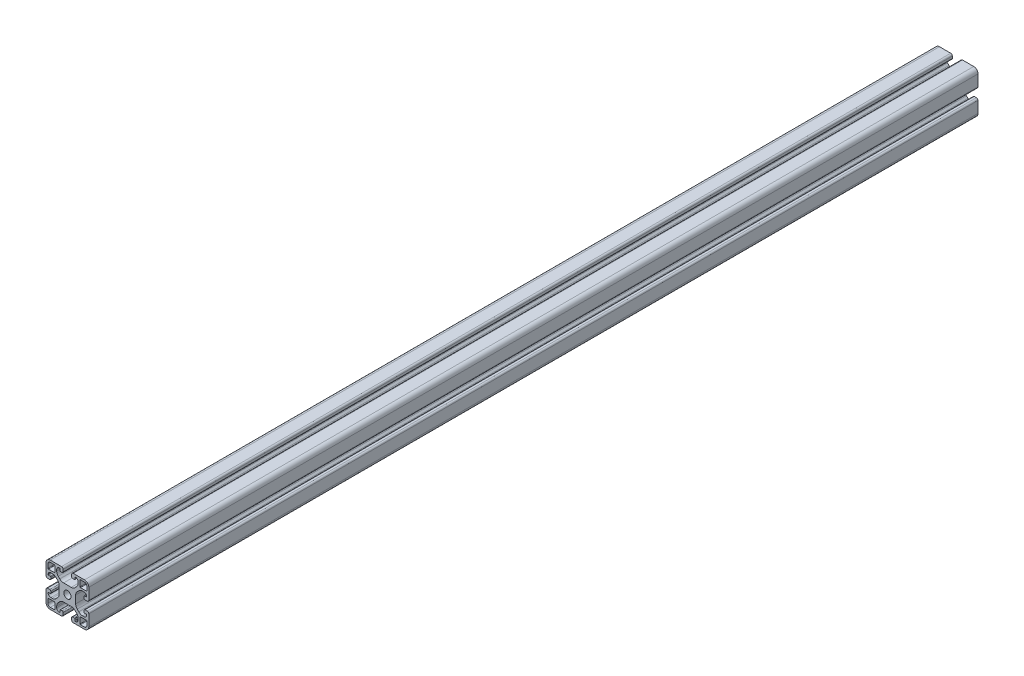
SolidWorks part; units mm, degrees
ref_plane "Plan de face" through (0, 0, 0) normal (0, 0, 1) x (1, 0, 0)
ref_plane "Plan de dessus" through (0, 0, 0) normal (0, 1, 0) x (1, 0, 0)
ref_plane "Plan de droite" through (0, 0, 0) normal (1, 0, 0) x (0, 0, -1)
ref_plane "Plan1" through (0, 0, -30) normal (0, 0, -1) x (-1, 0, 0)
sketch "Esquisse1" plane through (0, 0, -30) normal (0, 0, -1) x (-1, 0, 0)
  line L0 (-4.5, 15) -> (-4.5, 13.5)
  line L1 (-4, 13) -> (-2.5, 13)
  line L2 (-4.5, 10) -> (-5.8076, 10)
  line L3 (-9.3431, 11.4645) -> (-10.7855, 12.9069)
  line L4 (-12.25, 16.4424) -> (-12.25, 23.5576)
  line L5 (-10.7855, 27.0931) -> (-9.3431, 28.5355)
  line L6 (-5.8076, 30) -> (-4.5, 30)
  line L7 (-2.5, 27) -> (-4, 27)
  line L8 (-4.5, 26.5) -> (-4.5, 25)
  line L9 (-3.5, 24) -> (-1.5, 24)
  line L10 (0, 25.5) -> (0, 36)
  line L11 (-4, 40) -> (-14.5, 40)
  line L12 (-16, 38.5) -> (-16, 36.5)
  line L13 (-15, 35.5) -> (-13.5, 35.5)
  line L14 (-13, 36) -> (-13, 37.5)
  line L15 (-10, 35.5) -> (-10, 34.1924)
  line L16 (-11.4645, 30.6569) -> (-12.9069, 29.2145)
  line L17 (-16.4424, 27.75) -> (-23.5576, 27.75)
  line L18 (-27.0931, 29.2145) -> (-28.5355, 30.6569)
  line L19 (-30, 34.1924) -> (-30, 35.5)
  line L20 (-27, 37.5) -> (-27, 36)
  line L21 (-26.5, 35.5) -> (-25, 35.5)
  line L22 (-24, 36.5) -> (-24, 38.5)
  line L23 (-25.5, 40) -> (-36, 40)
  line L24 (-40, 36) -> (-40, 25.5)
  line L25 (-38.5, 24) -> (-36.5, 24)
  line L26 (-35.5, 25) -> (-35.5, 26.5)
  line L27 (-36, 27) -> (-37.5, 27)
  line L28 (-35.5, 30) -> (-34.1924, 30)
  line L29 (-30.6569, 28.5355) -> (-29.2145, 27.0931)
  line L30 (-27.75, 23.5576) -> (-27.75, 16.4424)
  line L31 (-29.2145, 12.9069) -> (-30.6569, 11.4645)
  line L32 (-34.1924, 10) -> (-35.5, 10)
  line L33 (-37.5, 13) -> (-36, 13)
  line L34 (-35.5, 13.5) -> (-35.5, 15)
  line L35 (-36.5, 16) -> (-38.5, 16)
  line L36 (-40, 14.5) -> (-40, 4)
  line L37 (-36, 0) -> (-25.5, 0)
  line L38 (-24, 1.5) -> (-24, 3.5)
  line L39 (-25, 4.5) -> (-26.5, 4.5)
  line L40 (-27, 4) -> (-27, 2.5)
  line L41 (-30, 4.5) -> (-30, 5.8076)
  line L42 (-28.5355, 9.3431) -> (-27.0931, 10.7855)
  line L43 (-23.5576, 12.25) -> (-16.4424, 12.25)
  line L44 (-12.9069, 10.7855) -> (-11.4645, 9.3431)
  line L45 (-10, 5.8076) -> (-10, 4.5)
  line L46 (-13, 2.5) -> (-13, 4)
  line L47 (-13.5, 4.5) -> (-15, 4.5)
  line L48 (-16, 3.5) -> (-16, 1.5)
  line L49 (-14.5, 0) -> (-4, 0)
  line L50 (0, 4) -> (0, 14.5)
  line L51 (-1.5, 16) -> (-3.5, 16)
  line L52 (-4, 1.8) -> (-7.7, 1.8)
  line L53 (-8.2, 2.3) -> (-8.2, 7.7)
  line L54 (-7.7, 8.2) -> (-2.3, 8.2)
  line L55 (-1.8, 7.7) -> (-1.8, 4)
  line L56 (-38.2, 4) -> (-38.2, 7.7)
  line L57 (-37.7, 8.2) -> (-32.3, 8.2)
  line L58 (-31.8, 7.7) -> (-31.8, 2.3)
  line L59 (-32.3, 1.8) -> (-36, 1.8)
  line L60 (-36, 38.2) -> (-32.3, 38.2)
  line L61 (-31.8, 37.7) -> (-31.8, 32.3)
  line L62 (-32.3, 31.8) -> (-37.7, 31.8)
  line L63 (-38.2, 32.3) -> (-38.2, 36)
  line L64 (-1.8, 36) -> (-1.8, 32.3)
  line L65 (-2.3, 31.8) -> (-7.7, 31.8)
  line L66 (-8.2, 32.3) -> (-8.2, 37.7)
  line L67 (-7.7, 38.2) -> (-4, 38.2)
  arc A0 (-4.5, 13.5) -> (-4, 13) centre (-4, 13.5) ccw
  arc A1 (-2.5, 13) -> (-2, 12.5) centre (-2.5, 12.5) cw
  arc A2 (-2, 12.5) -> (-4.5, 10) centre (-4.5, 12.5) cw
  arc A3 (-5.8076, 10) -> (-9.3431, 11.4645) centre (-5.8076, 15) cw
  arc A4 (-10.7855, 12.9069) -> (-12.25, 16.4424) centre (-7.25, 16.4424) cw
  arc A5 (-12.25, 23.5576) -> (-10.7855, 27.0931) centre (-7.25, 23.5576) cw
  arc A6 (-9.3431, 28.5355) -> (-5.8076, 30) centre (-5.8076, 25) cw
  arc A7 (-4.5, 30) -> (-2, 27.5) centre (-4.5, 27.5) cw
  arc A8 (-2, 27.5) -> (-2.5, 27) centre (-2.5, 27.5) cw
  arc A9 (-4, 27) -> (-4.5, 26.5) centre (-4, 26.5) ccw
  arc A10 (-4.5, 25) -> (-3.5, 24) centre (-3.5, 25) ccw
  arc A11 (-1.5, 24) -> (0, 25.5) centre (-1.5, 25.5) ccw
  arc A12 (0, 36) -> (-4, 40) centre (-4, 36) ccw
  arc A13 (-14.5, 40) -> (-16, 38.5) centre (-14.5, 38.5) ccw
  arc A14 (-16, 36.5) -> (-15, 35.5) centre (-15, 36.5) ccw
  arc A15 (-13.5, 35.5) -> (-13, 36) centre (-13.5, 36) ccw
  arc A16 (-13, 37.5) -> (-12.5, 38) centre (-12.5, 37.5) cw
  arc A17 (-12.5, 38) -> (-10, 35.5) centre (-12.5, 35.5) cw
  arc A18 (-10, 34.1924) -> (-11.4645, 30.6569) centre (-15, 34.1924) cw
  arc A19 (-12.9069, 29.2145) -> (-16.4424, 27.75) centre (-16.4424, 32.75) cw
  arc A20 (-23.5576, 27.75) -> (-27.0931, 29.2145) centre (-23.5576, 32.75) cw
  arc A21 (-28.5355, 30.6569) -> (-30, 34.1924) centre (-25, 34.1924) cw
  arc A22 (-30, 35.5) -> (-27.5, 38) centre (-27.5, 35.5) cw
  arc A23 (-27.5, 38) -> (-27, 37.5) centre (-27.5, 37.5) cw
  arc A24 (-27, 36) -> (-26.5, 35.5) centre (-26.5, 36) ccw
  arc A25 (-25, 35.5) -> (-24, 36.5) centre (-25, 36.5) ccw
  arc A26 (-24, 38.5) -> (-25.5, 40) centre (-25.5, 38.5) ccw
  arc A27 (-36, 40) -> (-40, 36) centre (-36, 36) ccw
  arc A28 (-40, 25.5) -> (-38.5, 24) centre (-38.5, 25.5) ccw
  arc A29 (-36.5, 24) -> (-35.5, 25) centre (-36.5, 25) ccw
  arc A30 (-35.5, 26.5) -> (-36, 27) centre (-36, 26.5) ccw
  arc A31 (-37.5, 27) -> (-38, 27.5) centre (-37.5, 27.5) cw
  arc A32 (-38, 27.5) -> (-35.5, 30) centre (-35.5, 27.5) cw
  arc A33 (-34.1924, 30) -> (-30.6569, 28.5355) centre (-34.1924, 25) cw
  arc A34 (-29.2145, 27.0931) -> (-27.75, 23.5576) centre (-32.75, 23.5576) cw
  arc A35 (-27.75, 16.4424) -> (-29.2145, 12.9069) centre (-32.75, 16.4424) cw
  arc A36 (-30.6569, 11.4645) -> (-34.1924, 10) centre (-34.1924, 15) cw
  arc A37 (-35.5, 10) -> (-38, 12.5) centre (-35.5, 12.5) cw
  arc A38 (-38, 12.5) -> (-37.5, 13) centre (-37.5, 12.5) cw
  arc A39 (-36, 13) -> (-35.5, 13.5) centre (-36, 13.5) ccw
  arc A40 (-35.5, 15) -> (-36.5, 16) centre (-36.5, 15) ccw
  arc A41 (-38.5, 16) -> (-40, 14.5) centre (-38.5, 14.5) ccw
  arc A42 (-40, 4) -> (-36, 0) centre (-36, 4) ccw
  arc A43 (-25.5, 0) -> (-24, 1.5) centre (-25.5, 1.5) ccw
  arc A44 (-24, 3.5) -> (-25, 4.5) centre (-25, 3.5) ccw
  arc A45 (-26.5, 4.5) -> (-27, 4) centre (-26.5, 4) ccw
  arc A46 (-27, 2.5) -> (-27.5, 2) centre (-27.5, 2.5) cw
  arc A47 (-27.5, 2) -> (-30, 4.5) centre (-27.5, 4.5) cw
  arc A48 (-30, 5.8076) -> (-28.5355, 9.3431) centre (-25, 5.8076) cw
  arc A49 (-27.0931, 10.7855) -> (-23.5576, 12.25) centre (-23.5576, 7.25) cw
  arc A50 (-16.4424, 12.25) -> (-12.9069, 10.7855) centre (-16.4424, 7.25) cw
  arc A51 (-11.4645, 9.3431) -> (-10, 5.8076) centre (-15, 5.8076) cw
  arc A52 (-10, 4.5) -> (-12.5, 2) centre (-12.5, 4.5) cw
  arc A53 (-12.5, 2) -> (-13, 2.5) centre (-12.5, 2.5) cw
  arc A54 (-13, 4) -> (-13.5, 4.5) centre (-13.5, 4) ccw
  arc A55 (-15, 4.5) -> (-16, 3.5) centre (-15, 3.5) ccw
  arc A56 (-16, 1.5) -> (-14.5, 0) centre (-14.5, 1.5) ccw
  arc A57 (-4, 0) -> (0, 4) centre (-4, 4) ccw
  arc A58 (0, 14.5) -> (-1.5, 16) centre (-1.5, 14.5) ccw
  arc A59 (-3.5, 16) -> (-4.5, 15) centre (-3.5, 15) ccw
  circle A60 centre (-20, 20) radius 3.4
  arc A61 (-1.8, 4) -> (-4, 1.8) centre (-4, 4) cw
  arc A62 (-7.7, 1.8) -> (-8.2, 2.3) centre (-7.7, 2.3) cw
  arc A63 (-8.2, 7.7) -> (-7.7, 8.2) centre (-7.7, 7.7) cw
  arc A64 (-2.3, 8.2) -> (-1.8, 7.7) centre (-2.3, 7.7) cw
  arc A65 (-36, 1.8) -> (-38.2, 4) centre (-36, 4) cw
  arc A66 (-38.2, 7.7) -> (-37.7, 8.2) centre (-37.7, 7.7) cw
  arc A67 (-32.3, 8.2) -> (-31.8, 7.7) centre (-32.3, 7.7) cw
  arc A68 (-31.8, 2.3) -> (-32.3, 1.8) centre (-32.3, 2.3) cw
  arc A69 (-38.2, 36) -> (-36, 38.2) centre (-36, 36) cw
  arc A70 (-32.3, 38.2) -> (-31.8, 37.7) centre (-32.3, 37.7) cw
  arc A71 (-31.8, 32.3) -> (-32.3, 31.8) centre (-32.3, 32.3) cw
  arc A72 (-37.7, 31.8) -> (-38.2, 32.3) centre (-37.7, 32.3) cw
  arc A73 (-4, 38.2) -> (-1.8, 36) centre (-4, 36) cw
  arc A74 (-1.8, 32.3) -> (-2.3, 31.8) centre (-2.3, 32.3) cw
  arc A75 (-7.7, 31.8) -> (-8.2, 32.3) centre (-7.7, 32.3) cw
  arc A76 (-8.2, 37.7) -> (-7.7, 38.2) centre (-7.7, 37.7) cw
extrude "Boss.-Extru.1" add sketch "Esquisse1" against normal blind 831.3
